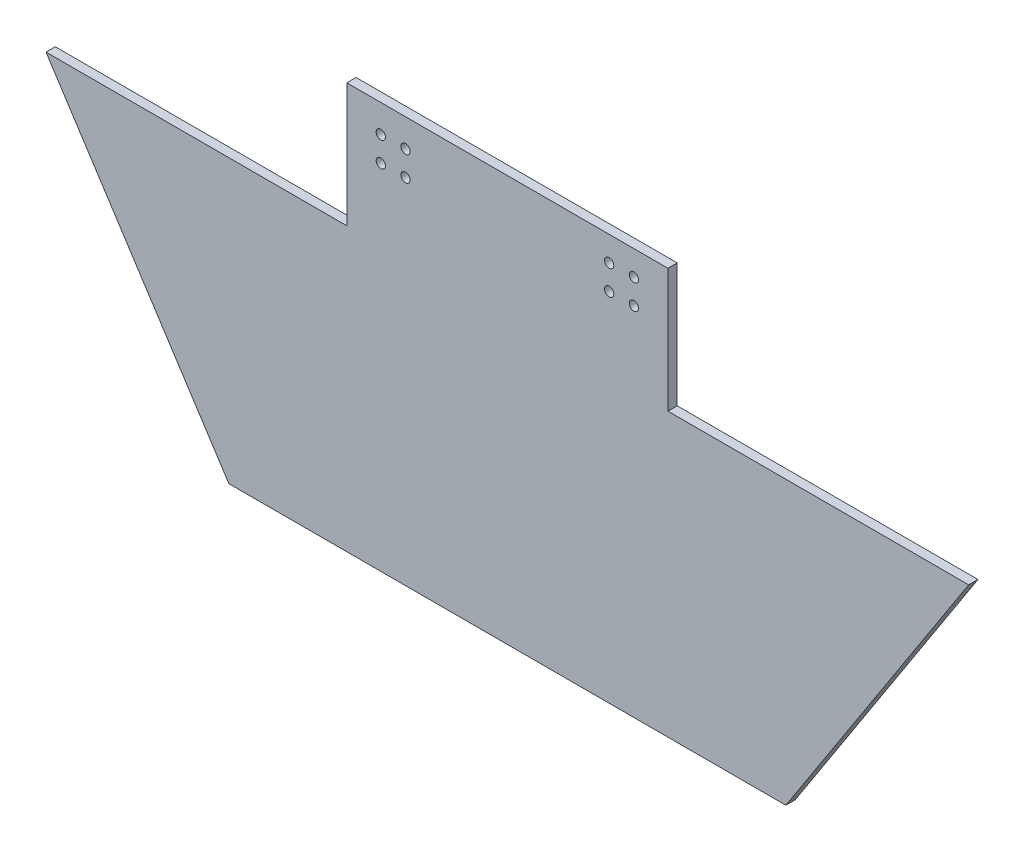
SolidWorks part; units mm, degrees
ref_plane "前视基准面" through (0, 0, 0) normal (0, 0, 1) x (1, 0, 0)
ref_plane "上视基准面" through (0, 0, 0) normal (0, 1, 0) x (1, 0, 0)
ref_plane "右视基准面" through (0, 0, 0) normal (1, 0, 0) x (0, 0, -1)
other "Configuration Table"
sketch "草图1" plane through (0, 0, 0) normal (0, 0, 1) x (1, 0, 0)
  line L0 (100, 0) -> (250, 0)
  line L1 (330.5697, -30) -> (265, -131.2381)
  line L2 (265, -131.2381) -> (85, -131.2381)
  line L3 (85, -131.2381) -> (19.4303, -30)
  line L4 (19.4303, -30) -> (100, -30)
  line L5 (100, -30) -> (100, 0)
  line L6 (250, 0) -> (250, -30)
  line L7 (250, -30) -> (330.5697, -30)
  dimension "D2" = 180
  dimension "D5" = 122.93
  dimension "D6" = 122.93
  dimension "D9" = 30
  dimension "D10" = 30
extrude "凸台-拉伸1" add sketch "草图1" along normal blind 3
sketch "草图2" plane through (0, 0, 3) normal (0, 0, 1) x (1, 0, 0)
  line L1 (250, -40) -> (324.0929, -40)
  line L2 (265, -131.2381) -> (330.5697, -30) construction
  line L4 (100, -40) -> (25.9071, -40)
  line L5 (19.4303, -30) -> (85, -131.2381) construction
  line L6 (25.9071, -40) -> (19.4303, -30)
  line L7 (19.4303, -30) -> (100, -30)
  line L8 (250, -30) -> (330.5697, -30)
  line L9 (330.5697, -30) -> (324.0929, -40)
  line L10 (100, 0) -> (123.1, 0)
  line L11 (250, 0) -> (100, 0) construction
  line L12 (123.1, 0) -> (123.1, -40)
  line L13 (123.1, -40) -> (100, -40)
  line L14 (100, 0) -> (100, -30)
  line L16 (250, 0) -> (226.9, 0)
  line L17 (226.9, 0) -> (226.9, -40)
  line L18 (226.9, -40) -> (250, -40)
  line L19 (250, 0) -> (250, -30)
  dimension "D1" = 10
  dimension "D2" = 10
  dimension "D3" = 40
  dimension "D4" = 40
  dimension "D5" = 23.1
  dimension "D6" = 23.1
extrude "切除-拉伸1" cut sketch "草图2" against normal blind 10
sketch "草图3" plane through (0, 0, 3) normal (0, 0, 1) x (1, 0, 0)
  line L0 (226.9, 0) -> (123.1, 0) construction
  line L1 (123.1, -40) -> (123.1, 0) construction
  line L2 (226.9, 0) -> (226.9, -40) construction
  circle A0 centre (134.1, -9) radius 1.5
  circle A1 centre (134.1, -17) radius 1.5
  circle A2 centre (142.1, -9) radius 1.5
  circle A3 centre (142.1, -17) radius 1.5
  circle A4 centre (207.9, -8) radius 1.5
  circle A5 centre (215.9, -8) radius 1.5
  circle A6 centre (207.9, -16) radius 1.5
  circle A7 centre (215.9, -16) radius 1.5
  dimension "D1" = 3
  dimension "D10" = 3
  dimension "D11" = 3
  dimension "D12" = 3
  dimension "D13" = 3
  dimension "D2" = 9
  dimension "D3" = 11
  dimension "D4" = 8
  dimension "D5" = 8
  dimension "D6" = 0
  dimension "D7" = 0
  dimension "D8" = 0
  dimension "D9" = 0
  dimension "D14" = 8
  dimension "D15" = 8
  dimension "D16" = 8
  dimension "D17" = 8
  dimension "D18" = 11
  dimension "D19" = 8
extrude "切除-拉伸2" cut sketch "草图3" against normal blind 10
